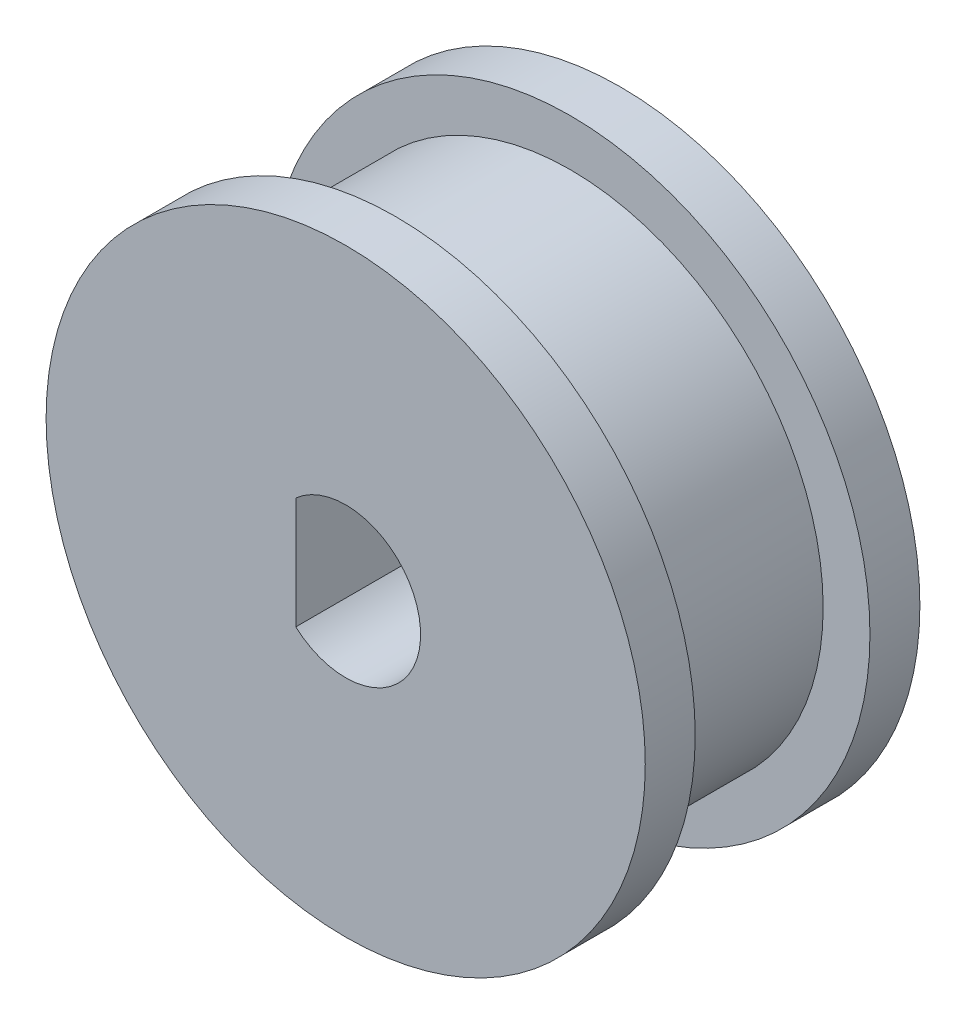
SolidWorks part; units mm, degrees
material "6061 合金"
ref_plane "前视基准面" through (0, 0, 0) normal (0, 0, 1) x (1, 0, 0)
ref_plane "上视基准面" through (0, 0, 0) normal (0, 1, 0) x (1, 0, 0)
ref_plane "右视基准面" through (0, 0, 0) normal (1, 0, 0) x (0, 0, -1)
sketch "草图1" plane through (0, 0, 0) normal (0, 0, 1) x (1, 0, 0)
  circle A0 centre (0, 0) radius 10.125
extrude "凸台-拉伸1" add sketch "草图1" along normal mid plane 7
sketch "草图2" plane through (0, 0, 3.5) normal (0, 0, 1) x (1, 0, 0)
  circle A0 centre (0, 0) radius 12
extrude "凸台-拉伸2" add sketch "草图2" along normal blind 2
mirror "镜向1" about plane through (0, 0, 0) normal (0, 0, 1) of "凸台-拉伸2"
sketch "草图3" plane through (0, 0, 5.5) normal (0, 0, 1) x (1, 0, 0)
  line L0 (0, 0) -> (-2, 0) construction
  line L1 (-2, 2.2361) -> (-2, -2.2361)
  arc A0 (-2, -2.2361) -> (-2, 2.2361) centre (0, 0) ccw
extrude "切除-拉伸1" cut sketch "草图3" against normal through all
sketch "草图4" plane through (0, 0, 0) normal (0, 1, 0) x (1, 0, 0)
  circle A0 centre (0, 0) radius 1.5
extrude "切除-拉伸2" cut sketch "草图4" against normal through all
